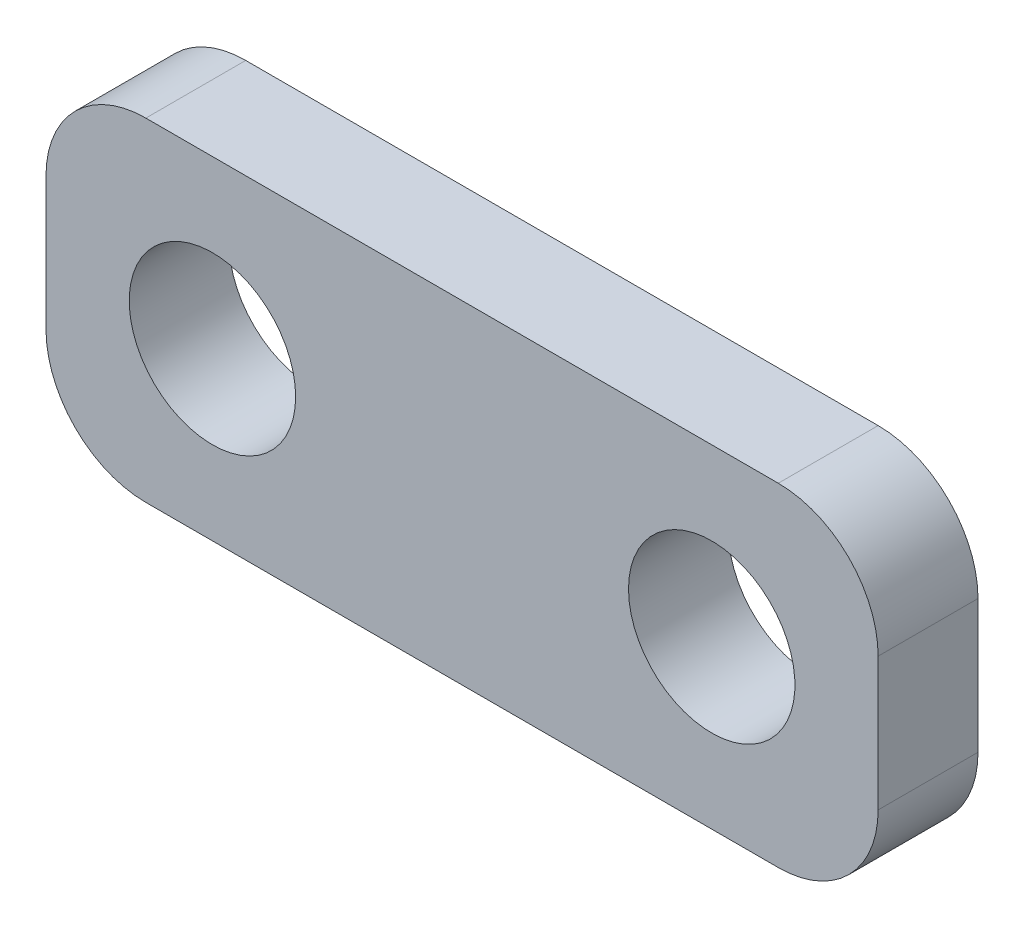
SolidWorks part; units mm, degrees
ref_plane "前视基准面" through (0, 0, 0) normal (0, 0, 1) x (1, 0, 0)
ref_plane "上视基准面" through (0, 0, 0) normal (0, 1, 0) x (1, 0, 0)
ref_plane "右视基准面" through (0, 0, 0) normal (1, 0, 0) x (0, 0, -1)
other "Configuration Table"
sketch "草图1" plane through (0, 0, 0) normal (0, 0, 1) x (1, 0, 0)
  line L0 (0, 5) -> (0, -5) construction
  line L1 (-12.5, -5) -> (12.5, -5)
  line L2 (-12.5, -5) -> (-12.5, 5)
  line L3 (-12.5, 5) -> (12.5, 5)
  line L4 (12.5, -5) -> (12.5, 5)
  line L5 (-12.5, -5) -> (12.5, 5) construction
  line L6 (-12.5, 5) -> (12.5, -5) construction
  circle A0 centre (-7.5, 0) radius 2.5
  circle A1 centre (7.5, 0) radius 2.5
  point P0 (0, 0)
  dimension "D3" = 5
  dimension "D1" = 25
  dimension "D2" = 10
  dimension "D4" = 7.5
extrude "凸台-拉伸1" add sketch "草图1" along normal blind 3
fillet "圆角1" radius 3 4 edges at (-12.5, -5, 1.5) (12.5, -5, 1.5) (12.5, 5, 1.5) (-12.5, 5, 1.5)
sketch "草图2" plane through (0, 0, 0) normal (0, 0, -1) x (-1, 0, 0)
  circle A0 centre (-7.5, 0) radius 2.5
sketch "草图3" plane through (0, 0, 0) normal (0, 1, 0) x (1, 0, 0)
  line L0 (7.5, 0) -> (7.5, -4.7683) construction
sketch "草图5" plane through (0, 0, 0) normal (0, 0, -1) x (-1, 0, 0)
  circle A0 centre (7.5, 0) radius 2.5
sketch "草图6" plane through (0, 0, 0) normal (0, 1, 0) x (1, 0, 0)
  line L0 (-7.5, 0) -> (-7.5, -5.8119) construction
  line L1 (-5, 0) -> (-10, 0) construction
